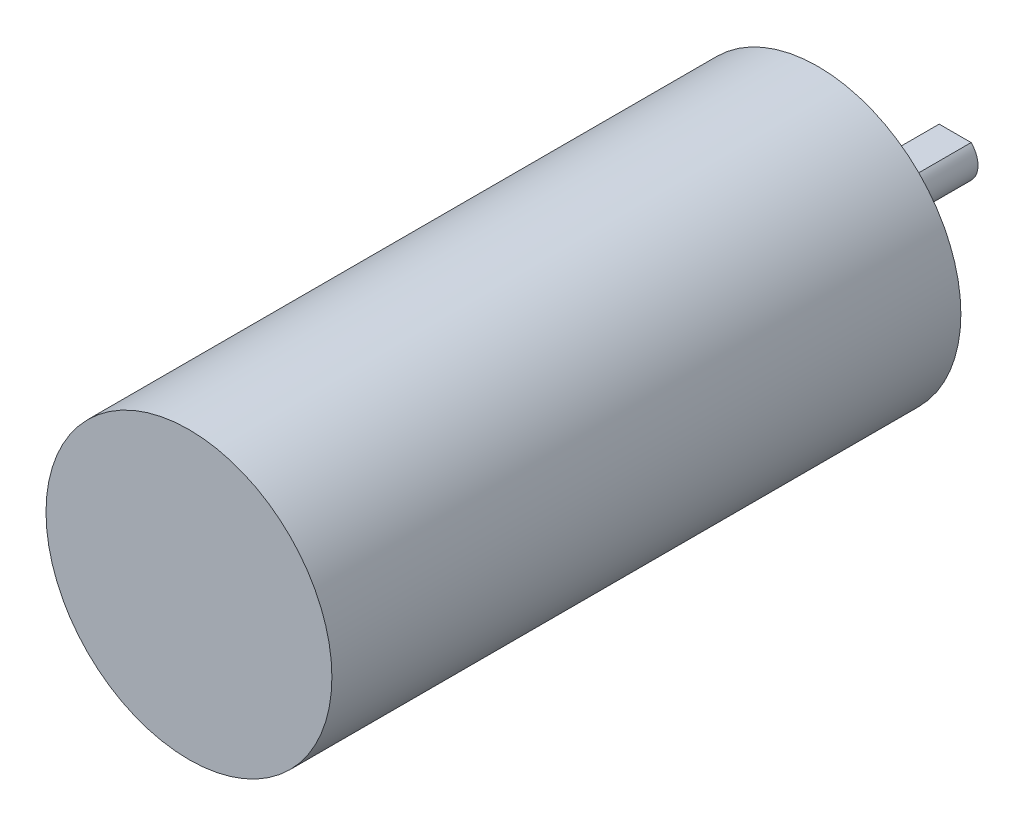
SolidWorks part; units mm, degrees
ref_plane "Front Plane" through (0, 0, 0) normal (0, 0, 1) x (1, 0, 0)
ref_plane "Top Plane" through (0, 0, 0) normal (0, 1, 0) x (1, 0, 0)
ref_plane "Right Plane" through (0, 0, 0) normal (1, 0, 0) x (0, 0, -1)
sketch "Sketch2" plane through (0, 0, 0) normal (0, 0, 1) x (1, 0, 0)
  circle A0 centre (0, 0) radius 12.5
  dimension "D1" = 25
extrude "Boss-Extrude1" add sketch "Sketch2" along normal blind 55
sketch "Sketch3" plane through (0, 0, 0) normal (0, 0, -1) x (-1, 0, 0)
  line L0 (-1.3982, 1.43) -> (1.3982, 1.43)
  arc A0 (-1.3982, 1.43) -> (1.3982, 1.43) centre (0, 0) ccw
  dimension "D1" = 4
  dimension "D2" = 1.43
extrude "Boss-Extrude2" add sketch "Sketch3" along normal blind 12
